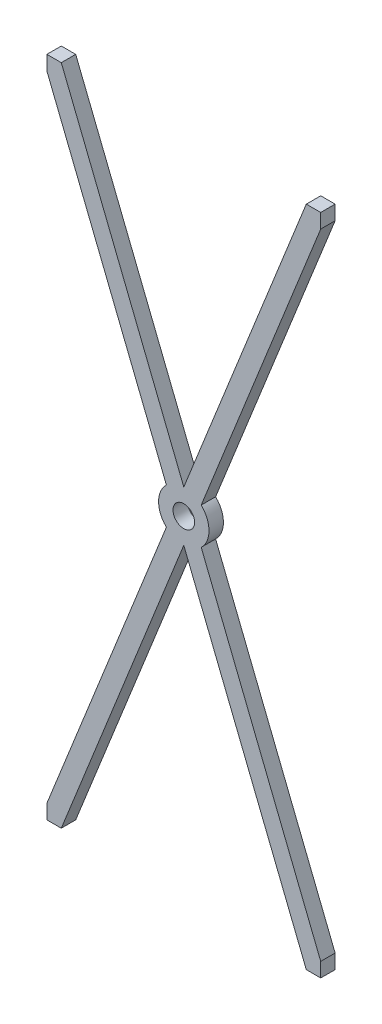
SolidWorks part; units mm, degrees
ref_plane "Ebene vorne" through (0, 0, 0) normal (0, 0, 1) x (1, 0, 0)
ref_plane "Ebene oben" through (0, 0, 0) normal (0, 1, 0) x (1, 0, 0)
ref_plane "Ebene rechts" through (0, 0, 0) normal (1, 0, 0) x (0, 0, -1)
sketch "Skizze1" plane through (0, 0, 0) normal (0, 0, 1) x (1, 0, 0)
  line L0 (0, 2300) -> (50, 2300)
  line L1 (0, 0) -> (50, 0)
  line L2 (0, 0) -> (0, 50)
  line L5 (50, 2300) -> (475, 1237.5)
  line L6 (950, 50) -> (950, 0)
  line L7 (900, 0) -> (475, 1062.5)
  line L8 (0, 2250) -> (0, 2300)
  line L9 (950, 2300) -> (900, 2300)
  line L10 (900, 2300) -> (475, 1237.5)
  line L12 (50, 0) -> (475, 1062.5)
  line L13 (950, 2250) -> (950, 2300)
  line L14 (440, 1150) -> (0, 50)
  line L15 (510, 1150) -> (950, 50)
  line L18 (900, 0) -> (950, 0)
  line L19 (440, 1150) -> (0, 2250)
  line L20 (510, 1150) -> (950, 2250)
  dimension "D1" = 950
  dimension "D2" = 2300
  dimension "D3" = 50
  dimension "D4" = 50
  dimension "D5" = 50
  dimension "D6" = 50
  dimension "D7" = 50
  dimension "D8" = 50
  dimension "D9" = 50
  dimension "D10" = 50
extrude "Aufsatz-Linear austragen1" add sketch "Skizze1" along normal blind 50
sketch "Skizze2" plane through (0, 0, 50) normal (0, 0, 1) x (1, 0, 0)
  circle A0 centre (475, 1150) radius 35
  circle A1 centre (475, 1150) radius 87.5
extrude "Aufsatz-Linear austragen2" add sketch "Skizze2" against normal blind 50
sketch "Skizze4" plane through (0, 0, 50) normal (0, 0, 1) x (1, 0, 0)
  line L0 (475, 1237.5) -> (475, 1062.5)
  circle A0 centre (475, 1150) radius 37.5
  dimension "D1" = 75
extrude "Schnitt-Linear austragen1" cut sketch "Skizze4" against normal blind 50 contours L0 A0 | L0 A0
